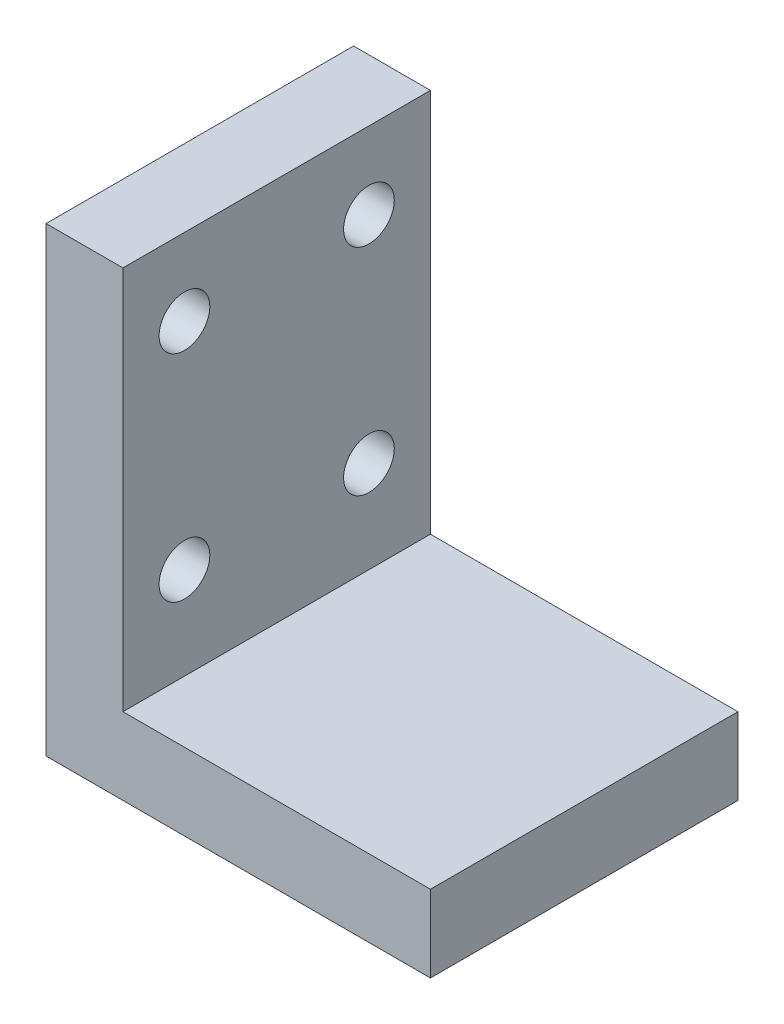
SolidWorks part; units mm, degrees
ref_plane "前视基准面" through (0, 0, 0) normal (0, 0, 1) x (1, 0, 0)
ref_plane "上视基准面" through (0, 0, 0) normal (0, 1, 0) x (1, 0, 0)
ref_plane "右视基准面" through (0, 0, 0) normal (1, 0, 0) x (0, 0, -1)
other "Configuration Table"
sketch "草图1" plane through (0, 0, 0) normal (0, 0, 1) x (1, 0, 0)
  line L0 (0, 30) -> (0, 0)
  line L1 (0, 0) -> (25, 0)
  line L2 (25, 0) -> (25, 5)
  line L3 (25, 5) -> (5, 5)
  line L5 (5, 5) -> (5, 30)
  line L6 (5, 30) -> (0, 30)
  point P4 (3.3946, 5.0097)
  point P9 (3.6245, 5.0097)
  dimension "D1" = 25
  dimension "D2" = 30
  dimension "D3" = 5
  dimension "D4" = 5
extrude "凸台-拉伸1" add sketch "草图1" along normal blind 20
sketch "草图2" plane through (5, 0, 0) normal (1, 0, 0) x (0, 0, -1)
  line L0 (0, 5) -> (0, 30) construction
  line L1 (-4, 25) -> (-16, 25) construction
  line L2 (-4, 25) -> (-4, 11) construction
  line L3 (-4, 11) -> (-16, 11) construction
  line L4 (-16, 25) -> (-16, 11) construction
  line L5 (-20, 30) -> (0, 30) construction
  circle A0 centre (-16, 25) radius 1.65
  circle A1 centre (-4, 25) radius 1.65
  circle A2 centre (-4, 11) radius 1.65
  circle A3 centre (-16, 11) radius 1.65
  dimension "D5" = 3.3
  dimension "D1" = 12
  dimension "D2" = 14
  dimension "D3" = 4
  dimension "D4" = 5
extrude "切除-拉伸1" cut sketch "草图2" against normal blind 20
